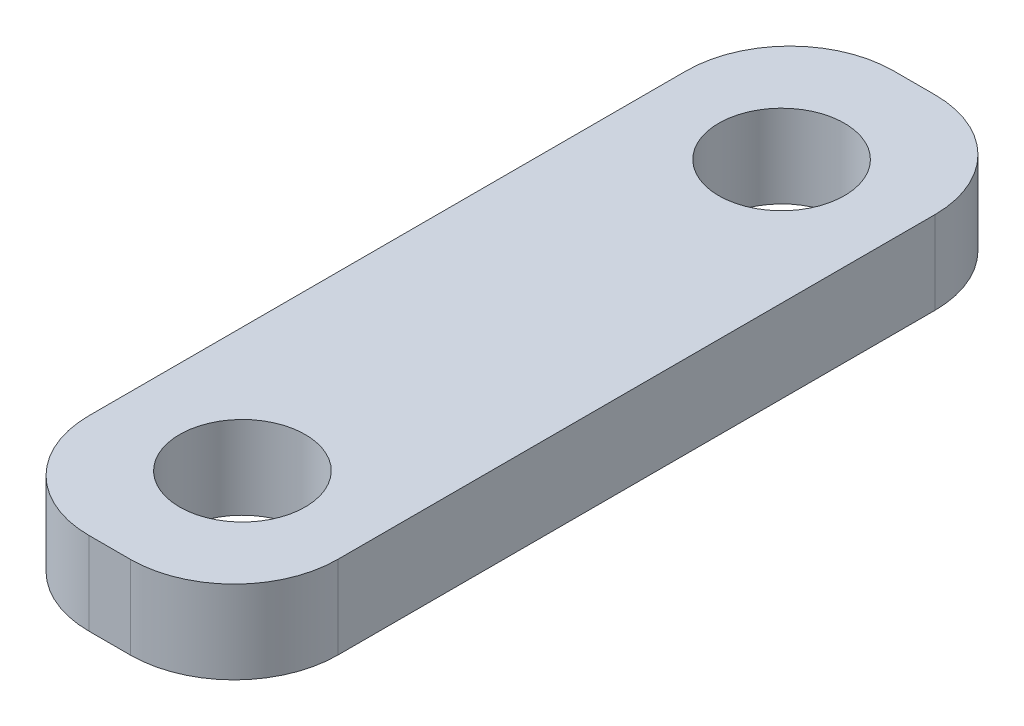
SolidWorks part; units mm, degrees
ref_plane "前视基准面" through (0, 0, 0) normal (0, 0, 1) x (1, 0, 0)
ref_plane "上视基准面" through (0, 0, 0) normal (0, 1, 0) x (1, 0, 0)
ref_plane "右视基准面" through (0, 0, 0) normal (1, 0, 0) x (0, 0, -1)
other "Configuration Table"
ref_plane "基准面1" through (0, 0, 0) normal (0, -1, 0) x (1, 0, 0)
sketch "草图1" plane through (0, 0, 0) normal (0, -1, 0) x (1, 0, 0)
  line L0 (6, -16.9) -> (6, -2.5)
  line L1 (3.5, 0) -> (2.5, 0)
  line L2 (0, -2.5) -> (0, -16.9)
  line L3 (2.5, -19.4) -> (3.5, -19.4)
  circle A0 centre (3, -3.2) radius 1.515
  circle A1 centre (3, -16.2) radius 1.515
  arc A2 (6, -2.5) -> (3.5, 0) centre (3.5, -2.5) ccw
  arc A3 (2.5, 0) -> (0, -2.5) centre (2.5, -2.5) ccw
  arc A4 (0, -16.9) -> (2.5, -19.4) centre (2.5, -16.9) ccw
  arc A5 (3.5, -19.4) -> (6, -16.9) centre (3.5, -16.9) ccw
  dimension "D1" = 3.03
  dimension "D2" = 3.03
  dimension "D3" = 2.5
  dimension "D4" = 3
  dimension "D5" = 6
  dimension "D6" = 3.2
  dimension "D7" = 16.2
  dimension "D8" = 19.4
extrude "凸台-拉伸1" add sketch "草图1" against normal blind 2
